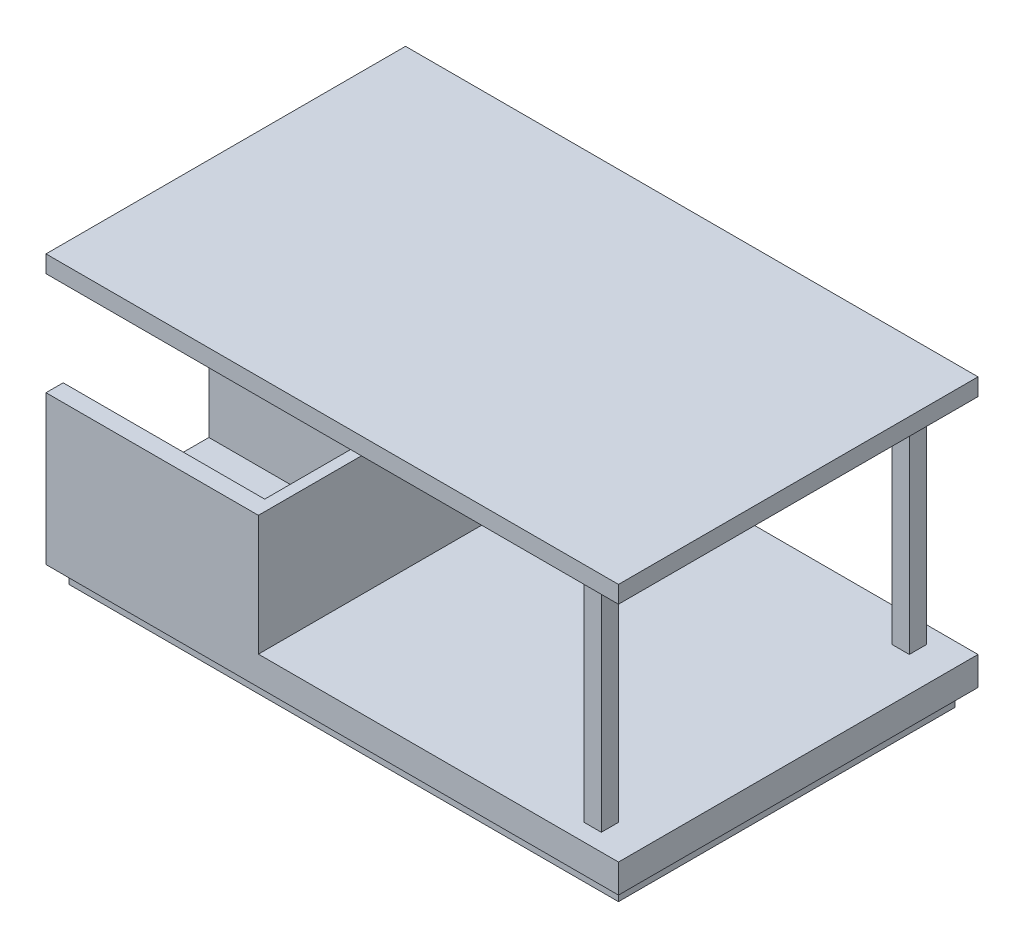
SolidWorks part; units mm, degrees
ref_plane "Front Plane" through (0, 0, 0) normal (0, 0, 1) x (1, 0, 0)
ref_plane "Top Plane" through (0, 0, 0) normal (0, 1, 0) x (1, 0, 0)
ref_plane "Right Plane" through (0, 0, 0) normal (1, 0, 0) x (0, 0, -1)
sketch "Sketch1" plane through (0, 0, 0) normal (0, 1, 0) x (1, 0, 0)
  line L1 (-500, 314) -> (500, 314)
  line L2 (-500, 314) -> (-500, -314)
  line L3 (-500, -314) -> (500, -314)
  line L4 (500, 314) -> (500, -314)
  line L9 (-500, 314) -> (128, 314)
  line L10 (-500, 314) -> (-500, -314)
  line L11 (-500, -314) -> (128, -314)
  line L13 (128, 314) -> (500, 314)
  line L15 (128, -314) -> (500, -314)
  line L16 (500, 314) -> (500, -314)
extrude "Boss-Extrude1" add sketch "Sketch1" along normal blind 50 contours L2 L1 L4 L3
sketch "Sketch2" plane through (0, 50, 0) normal (0, 1, 0) x (1, 0, 0)
  line L0 (-500, -314) -> (500, -314) construction
  line L1 (500, 314) -> (-129, 314)
  line L2 (500, 314) -> (500, -314)
  line L3 (500, -314) -> (-129, -314)
  line L4 (-129, 314) -> (-129, -314)
  line L6 (-129, 314) -> (-500, 314)
  line L7 (-129, 314) -> (-129, -314)
  line L8 (-129, -314) -> (-500, -314)
  line L9 (-500, 314) -> (-500, -314)
  line M5 (-500, -314) -> (500, -314)
  line M7 (500, 314) -> (-500, 314)
  line M8 (-500, 314) -> (-500, -314)
extrude "Boss-Extrude2" add sketch "Sketch2" along normal blind 210 contours L4 M7 M8 M5
sketch "Sketch3" plane through (-500, 0, 0) normal (-1, 0, 0) x (0, 0, 1)
  line L0 (-314, 0) -> (314, 0) construction
  line L1 (-314, 260) -> (-285, 260)
  line L2 (-314, 260) -> (-314, 0)
  line L3 (-314, 0) -> (-285, 0)
  line L4 (-285, 260) -> (-285, 0)
  line L6 (314, 260) -> (284, 260)
  line L7 (314, 260) -> (314, 0)
  line L8 (314, 0) -> (284, 0)
  line L9 (284, 260) -> (284, 0)
  line L10 (-285, 0) -> (284, 0)
  line L12 (-285, 50) -> (284, 50)
  line L15 (-285, 260) -> (284, 260)
  line L19 (-285, 50) -> (284, 50)
  line L20 (-285, 50) -> (-285, 260)
  line L21 (-285, 260) -> (284, 260)
  line L22 (284, 50) -> (284, 260)
  line M7 (314, 260) -> (-314, 260)
extrude "Cut-Extrude1" cut sketch "Sketch3" against normal blind 352 contours L4 L12 L9 M7
sketch "Sketch4" plane through (0, 50, 0) normal (0, 1, 0) x (1, 0, 0)
  line L0 (-148, 285) -> (-500, -284)
  line L1 (-500, -284) -> (-500, 285)
  line L2 (-500, 285) -> (-148, -284)
  line L3 (-324, 0.5) -> (-324, 30.5)
  line L4 (-324, 0.5) -> (-324, -29.5)
  line L5 (-148, 285) -> (-148, -284) construction
  line L6 (-324, 30.5) -> (-148, 30.5)
  line L7 (-324, 30.5) -> (-324, -29.5)
  line L8 (-324, -29.5) -> (-148, -29.5)
  line L9 (-148, 30.5) -> (-148, -29.5)
  line L11 (-324, 30.5) -> (-500, 30.5)
  line L12 (-324, 30.5) -> (-324, -29.5)
  line L13 (-324, -29.5) -> (-500, -29.5)
  line L14 (-500, 30.5) -> (-500, -29.5)
  line M4 (-148, -284) -> (-148, 285)
extrude "Boss-Extrude3" add sketch "Sketch4" along normal blind 160 contours L13 L0 L2 L11 L1 | L2 L8 L6 L0 M4 | L4 L8 L2 | L13 L4 L0 | L6 L3 L0 | L3 L11 L2
sketch "Sketch6" plane through (500, 0, 0) normal (1, 0, 0) x (0, 0, -1)
  line L1 (-314, 50) -> (314, 50)
  line L2 (-314, 50) -> (-314, 470)
  line L3 (-314, 470) -> (314, 470)
  line L4 (314, 50) -> (314, 470)
  line L5 (-314, 470) -> (314, 470)
  line L6 (-314, 470) -> (-314, 440)
  line L7 (-314, 440) -> (314, 440)
  line L8 (314, 470) -> (314, 440)
extrude "Boss-Extrude4" add sketch "Sketch6" against normal blind 1000 separate body contours L6 L5 L8 L7
sketch "Sketch7" plane through (0, 210, 0) normal (0, 1, 0) x (1, 0, 0)
  line L0 (-148, -29.5) -> (-500, -29.5) construction
  line L1 (-500, 30.5) -> (-440, 30.5)
  line L2 (-500, 30.5) -> (-500, -29.5)
  line L3 (-500, -29.5) -> (-440, -29.5)
  line L4 (-440, 30.5) -> (-440, -29.5)
  line L5 (-380, 30.5) -> (-440, -29.5)
  line L6 (-440, 30.5) -> (-380, 30.5)
  line L7 (-440, 30.5) -> (-440, -29.5)
  line L8 (-440, -29.5) -> (-380, -29.5)
  line L9 (-380, 30.5) -> (-380, -29.5)
  line L10 (-440, 30.5) -> (-380, -29.5)
  circle A0 centre (-410, 0.5) radius 30
  circle A1 centre (-410, 0.5) radius 25
extrude "Boss-Extrude5" add sketch "Sketch7" along normal blind 242 contours L10 A1 L5 | L5 A1 L10 | L10 A1 L5 | L5 A1 L10
sketch "Sketch8" plane through (0, 440, 0) normal (0, -1, 0) x (-1, 0, 0)
  line L0 (500, 314) -> (-500, 314) construction
  line L1 (500, -314) -> (440, -314)
  line L2 (500, -314) -> (500, 314)
  line L3 (500, 314) -> (440, 314)
  line L4 (440, -314) -> (440, 314)
  line L5 (-500, -314) -> (-500, 314) construction
  line L6 (440, 314) -> (-500, 314)
  line L7 (440, 314) -> (440, 284)
  line L8 (440, 284) -> (-500, 284)
  line L9 (-500, 314) -> (-500, 284)
  line L11 (440, -314) -> (-500, -314)
  line L12 (440, -314) -> (440, -284)
  line L13 (440, -284) -> (-500, -284)
  line L14 (-500, -314) -> (-500, -284)
  line L15 (-500, -284) -> (-440, -284)
  line L16 (-500, -284) -> (-500, 284)
  line L17 (-500, 284) -> (-440, 284)
  line L18 (-440, -284) -> (-440, 284)
  line L19 (-440, -284) -> (-410, -284)
  line L20 (-440, -284) -> (-440, 284)
  line L21 (-440, 284) -> (-410, 284)
  line L22 (-410, -284) -> (-410, 284)
  line L23 (-410, -284) -> (440, -284)
  line L24 (-410, -284) -> (-410, -254)
  line L25 (-410, -254) -> (440, -254)
  line L26 (440, -284) -> (440, -254)
  line L27 (440, -254) -> (380, -254)
  line L28 (440, -254) -> (440, 284)
  line L29 (440, 284) -> (380, 284)
  line L30 (380, -254) -> (380, 284)
  line L31 (380, 284) -> (-410, 284)
  line L32 (380, 284) -> (380, 254)
  line L33 (380, 254) -> (-410, 254)
  line L34 (-410, 284) -> (-410, 254)
  circle M9 centre (410, 0.5) radius 25
extrude "Boss-Extrude6" add sketch "Sketch8" along normal blind 30 contours L13 L22 L8 L18 | L25 L22 L13 L4 | L33 L30 L8 L22 | L30 L25 L4 L8 M9
sketch "Sketch9" plane through (0, 410, 0) normal (0, -1, 0) x (-1, 0, 0)
  line L0 (-440, -284) -> (-440, 284) construction
  line L1 (-410, -254) -> (-440, -254)
  line L2 (-410, -254) -> (-410, -284)
  line L3 (-410, -284) -> (-440, -284)
  line L4 (-440, -254) -> (-440, -284)
  line L5 (-410, 254) -> (-440, 254)
  line L6 (-410, 254) -> (-410, 284)
  line L7 (-410, 284) -> (-440, 284)
  line L8 (-440, 254) -> (-440, 284)
  line L9 (440, 284) -> (-440, 284) construction
extrude "Boss-Extrude7" add sketch "Sketch9" along normal blind 388
sketch "Sketch10" plane through (0, 0, 0) normal (0, -1, 0) x (-1, 0, 0)
  line L0 (-500, 314) -> (-500, -314) construction
  line L1 (500, 314) -> (-500, 314)
  line L2 (500, 314) -> (500, 294)
  line L3 (500, 294) -> (-500, 294)
  line L4 (-500, 314) -> (-500, 294)
  line L6 (500, -314) -> (-500, -314)
  line L7 (500, -314) -> (500, -294)
  line L8 (500, -294) -> (-500, -294)
  line L9 (-500, -314) -> (-500, -294)
  line L10 (500, 294) -> (480, 294)
  line L11 (500, 294) -> (500, -294)
  line L12 (500, -294) -> (480, -294)
  line L13 (480, 294) -> (480, -294)
  line L14 (-500, 294) -> (-480, 294)
  line L15 (-500, 294) -> (-500, -294)
  line L16 (-500, -294) -> (-480, -294)
  line L17 (-480, 294) -> (-480, -294)
  line L18 (480, 294) -> (-480, 294)
  line L19 (480, 294) -> (480, 264)
  line L20 (480, 264) -> (-480, 264)
  line L21 (-480, 294) -> (-480, 264)
  line L22 (480, 264) -> (450, 264)
  line L23 (480, 264) -> (480, -294)
  line L24 (480, -294) -> (450, -294)
  line L25 (450, 264) -> (450, -294)
  line L26 (-480, 264) -> (-450, 264)
  line L27 (-480, 264) -> (-480, -294)
  line L28 (-480, -294) -> (-450, -294)
  line L29 (-450, 264) -> (-450, -294)
  line L30 (450, -294) -> (-450, -294)
  line L31 (450, -294) -> (450, -264)
  line L32 (450, -264) -> (-450, -264)
  line L33 (-450, -294) -> (-450, -264)
extrude "Boss-Extrude8" add sketch "Sketch10" along normal blind 30 contours L20 L25 L8 L13 | L20 L13 L3 L17 | L25 L32 L29 L8 | L29 L20 L17 L8
